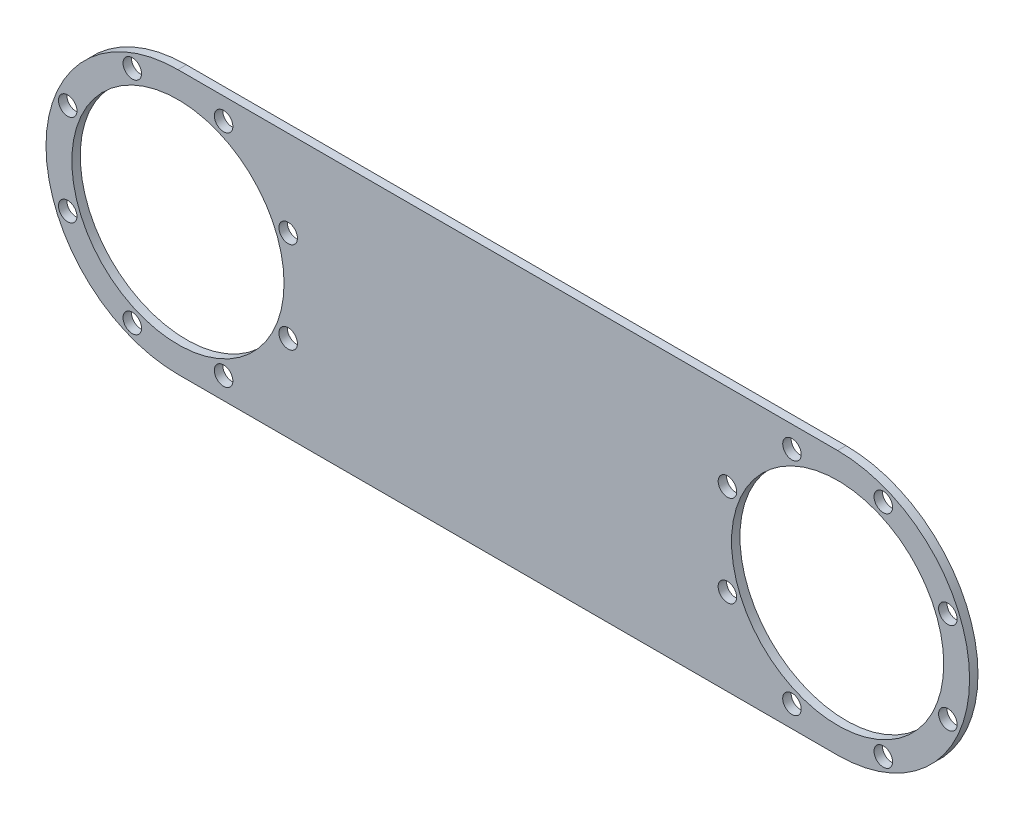
SolidWorks part; units mm, degrees
ref_plane "前视基准面" through (0, 0, 0) normal (0, 0, 1) x (1, 0, 0)
ref_plane "上视基准面" through (0, 0, 0) normal (0, 1, 0) x (1, 0, 0)
ref_plane "右视基准面" through (0, 0, 0) normal (1, 0, 0) x (0, 0, -1)
sketch "草图1" plane through (0, 0, 0) normal (0, 0, 1) x (1, 0, 0)
  line L0 (0, -47) -> (0, 47) construction
  line L1 (235, -47) -> (235, 47) construction
  line L6 (0, -47) -> (235, -47)
  line L10 (0, 47) -> (235, 47)
  circle A1 centre (16.264, -39.2649) radius 3.3
  circle A6 centre (16.264, -39.2649) radius 3.3
  circle A7 centre (39.2649, -16.264) radius 3.3
  circle A8 centre (39.2649, -16.264) radius 3.3
  circle A9 centre (39.2649, 16.264) radius 3.3
  circle A10 centre (39.2649, 16.264) radius 3.3
  circle A11 centre (16.264, 39.2649) radius 3.3
  circle A12 centre (16.264, 39.2649) radius 3.3
  circle A13 centre (-16.264, 39.2649) radius 3.3
  circle A14 centre (-16.264, 39.2649) radius 3.3
  circle A15 centre (-39.2649, 16.264) radius 3.3
  circle A16 centre (-39.2649, 16.264) radius 3.3
  circle A17 centre (-39.2649, -16.264) radius 3.3
  circle A18 centre (-39.2649, -16.264) radius 3.3
  circle A19 centre (-16.264, -39.2649) radius 3.3
  circle A20 centre (-16.264, -39.2649) radius 3.3
  circle A21 centre (251.264, -39.2649) radius 3.3
  circle A26 centre (251.264, -39.2649) radius 3.3
  circle A27 centre (274.2649, -16.264) radius 3.3
  circle A28 centre (274.2649, -16.264) radius 3.3
  circle A29 centre (274.2649, 16.264) radius 3.3
  circle A30 centre (274.2649, 16.264) radius 3.3
  circle A31 centre (251.264, 39.2649) radius 3.3
  circle A32 centre (251.264, 39.2649) radius 3.3
  circle A33 centre (218.736, 39.2649) radius 3.3
  circle A34 centre (218.736, 39.2649) radius 3.3
  circle A35 centre (195.7351, 16.264) radius 3.3
  circle A36 centre (195.7351, 16.264) radius 3.3
  circle A37 centre (195.7351, -16.264) radius 3.3
  circle A38 centre (195.7351, -16.264) radius 3.3
  circle A39 centre (218.736, -39.2649) radius 3.3
  circle A40 centre (218.736, -39.2649) radius 3.3
  circle A42 centre (0, 0) radius 37.8
  circle A43 centre (235, 0) radius 37.8
  circle A44 centre (235, 0) radius 7.5 construction
  arc A45 (239.5, -37.5312) -> (230.5, -37.5312) centre (235, 0) ccw construction
  arc A46 (0, -47) -> (0, 47) centre (0, 0) cw
  circle A47 centre (0, 0) radius 47 construction
  arc A48 (235, -47) -> (235, 47) centre (235, 0) ccw
  circle A49 centre (235, 0) radius 47 construction
  dimension "D2" = 0
  dimension "D3" = 0
  dimension "D4" = 0
  dimension "D5" = 0
  dimension "D6" = 0
  dimension "D7" = 0
  dimension "D8" = 0
  dimension "D9" = 0
  dimension "D11" = 0
  dimension "D12" = 0
  dimension "D13" = 0
  dimension "D14" = 0
  dimension "D15" = 0
  dimension "D16" = 0
  dimension "D17" = 0
  dimension "D18" = 0
extrude "凸台-拉伸1" add sketch "草图1" along normal blind 3
